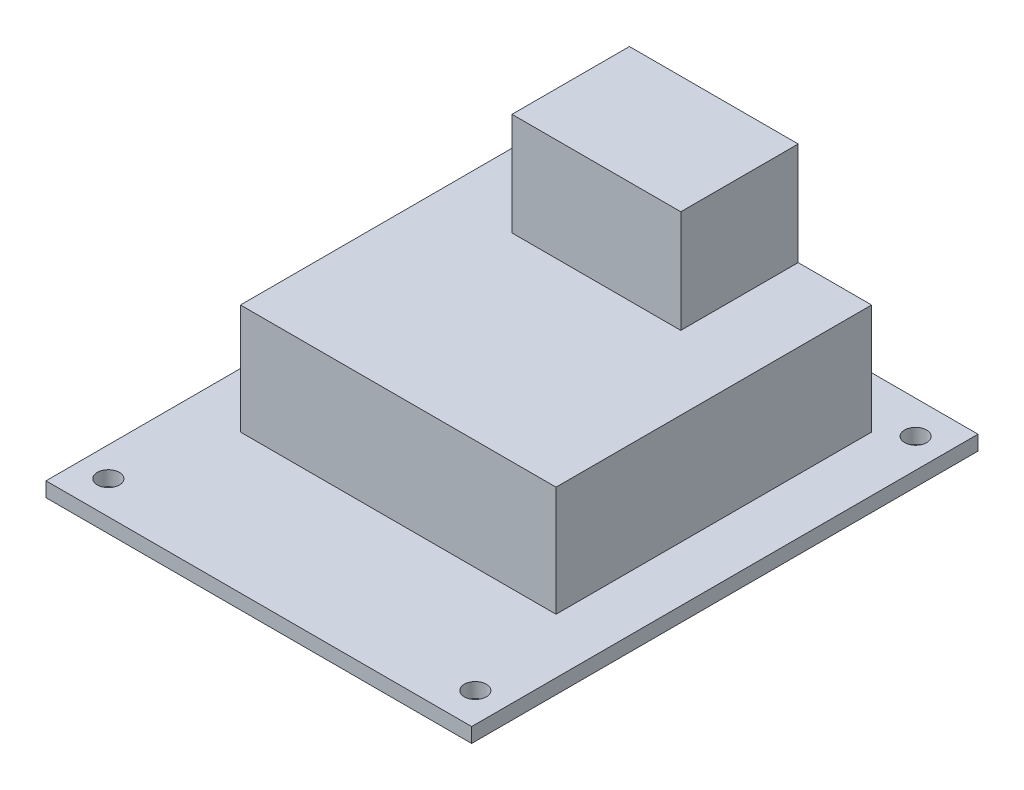
SolidWorks part; units mm, degrees
ref_plane "Спереди" through (0, 0, 0) normal (0, 0, 1) x (1, 0, 0)
ref_plane "Сверху" through (0, 0, 0) normal (0, 1, 0) x (1, 0, 0)
ref_plane "Справа" through (0, 0, 0) normal (1, 0, 0) x (0, 0, -1)
ref_plane "Плоскость4" through (0, 0, 0) normal (0, -1, 0) x (1, 0, 0)
sketch "Эскиз1" plane through (0, 0, 0) normal (0, -1, 0) x (1, 0, 0)
  line L0 (29, 34.5) -> (-29, 34.5)
  line L1 (-29, 34.5) -> (-29, -34.5)
  line L2 (-29, -34.5) -> (29, -34.5)
  line L3 (29, -34.5) -> (29, 34.5)
  line L4 (0, 34.5) -> (0, -34.5) construction
  line L6 (-29, 0) -> (29, 0) construction
  dimension "D1" = 58
  dimension "D2" = 69
extrude "плата" add sketch "Эскиз1" against normal blind 2
sketch "Эскиз2" plane through (0, 2, 0) normal (0, 1, 0) x (-1, 0, 0)
  line L0 (-21.5, -27.5) -> (-21.5, 15.5)
  line L1 (-21.5, 15.5) -> (21.5, 15.5)
  line L2 (21.5, 15.5) -> (21.5, -27.5)
  line L3 (21.5, -27.5) -> (-21.5, -27.5)
  line L4 (0, 34.5) -> (0, -34.5) construction
  line L5 (-29, 34.5) -> (29, 34.5) construction
  line L6 (29, -34.5) -> (-29, -34.5) construction
  line L7 (29, 0) -> (-29, 0) construction
  line L9 (29, 34.5) -> (29, -34.5) construction
  line L12 (-29, -34.5) -> (-29, 34.5) construction
  line L13 (21.5, -6) -> (-21.5, -6) construction
  point P14 (0, 15.5)
  dimension "D1" = 43
  dimension "D2" = 43
  dimension "D3" = 6
extrude "выступы сверху" add sketch "Эскиз2" along normal blind 15
sketch "Эскиз3" plane through (0, 17, 0) normal (0, 1, 0) x (-1, 0, 0)
  line L0 (-11.5, -11.5) -> (11.5, -11.5)
  line L1 (11.5, -11.5) -> (11.5, -27.5)
  line L2 (11.5, -27.5) -> (-11.5, -27.5)
  line L3 (-11.5, -27.5) -> (-11.5, -11.5)
  line L4 (0, 15.5) -> (0, -27.5) construction
  line L5 (21.5, 15.5) -> (-21.5, 15.5) construction
  line L6 (-21.5, -27.5) -> (21.5, -27.5) construction
  line L7 (-21.5, 15.5) -> (-21.5, -27.5) construction
  line L8 (-21.5, -6) -> (21.5, -6) construction
  line L9 (21.5, -27.5) -> (21.5, 15.5) construction
  point P8 (0, -11.5)
  dimension "D1" = 23
  dimension "D2" = 16
extrude "радиатор" add sketch "Эскиз3" along normal blind 14
sketch "Эскиз4" plane through (0, 0, 0) normal (0, -1, 0) x (1, 0, 0)
  line L0 (-20, -25) -> (-20, 25)
  line L1 (-20, 25) -> (20, 25)
  line L2 (20, 25) -> (20, -25)
  line L3 (20, -25) -> (-20, -25)
  line L4 (0, 34.5) -> (0, -34.5) construction
  line L5 (29, 34.5) -> (-29, 34.5) construction
  line L6 (-29, -34.5) -> (29, -34.5) construction
  line L8 (-29, 34.5) -> (-29, -34.5) construction
  line L9 (-29, 0) -> (29, 0) construction
  line L10 (29, -34.5) -> (29, 34.5) construction
  point P10 (0, 25)
  point P17 (20, 0)
  dimension "D1" = 40
  dimension "D2" = 50
extrude "выступы снизу" add sketch "Эскиз4" along normal blind 3
sketch "Эскиз7" plane through (0, 2, 0) normal (0, 1, 0) x (1, 0, 0)
  line L0 (0, 34.5) -> (0, -34.5) construction
  line L1 (-29, 34.5) -> (29, 34.5) construction
  line L2 (29, -34.5) -> (-29, -34.5) construction
  line L3 (-25, 0) -> (25, 0) construction
  line L4 (-29, -34.5) -> (-29, 34.5) construction
  line L5 (-29, 0) -> (29, 0) construction
  line L6 (29, 34.5) -> (29, -34.5) construction
  line L7 (-25, 30) -> (25, 30) construction
  line L8 (-25, 30) -> (-25, -30) construction
  line L9 (-25, -30) -> (25, -30) construction
  line L10 (25, 30) -> (25, -30) construction
  line L12 (0, -30) -> (0, 30) construction
  circle A0 centre (-25, 30) radius 1.5
  circle A1 centre (25, 30) radius 1.5
  circle A2 centre (25, -30) radius 1.5
  circle A3 centre (-25, -30) radius 1.5
  point P24 (0, 0)
  dimension "D1" = 3
  dimension "D2" = 50
  dimension "D3" = 60
extrude "крепежные отверстия" cut sketch "Эскиз7" against normal through all and the other way through all
